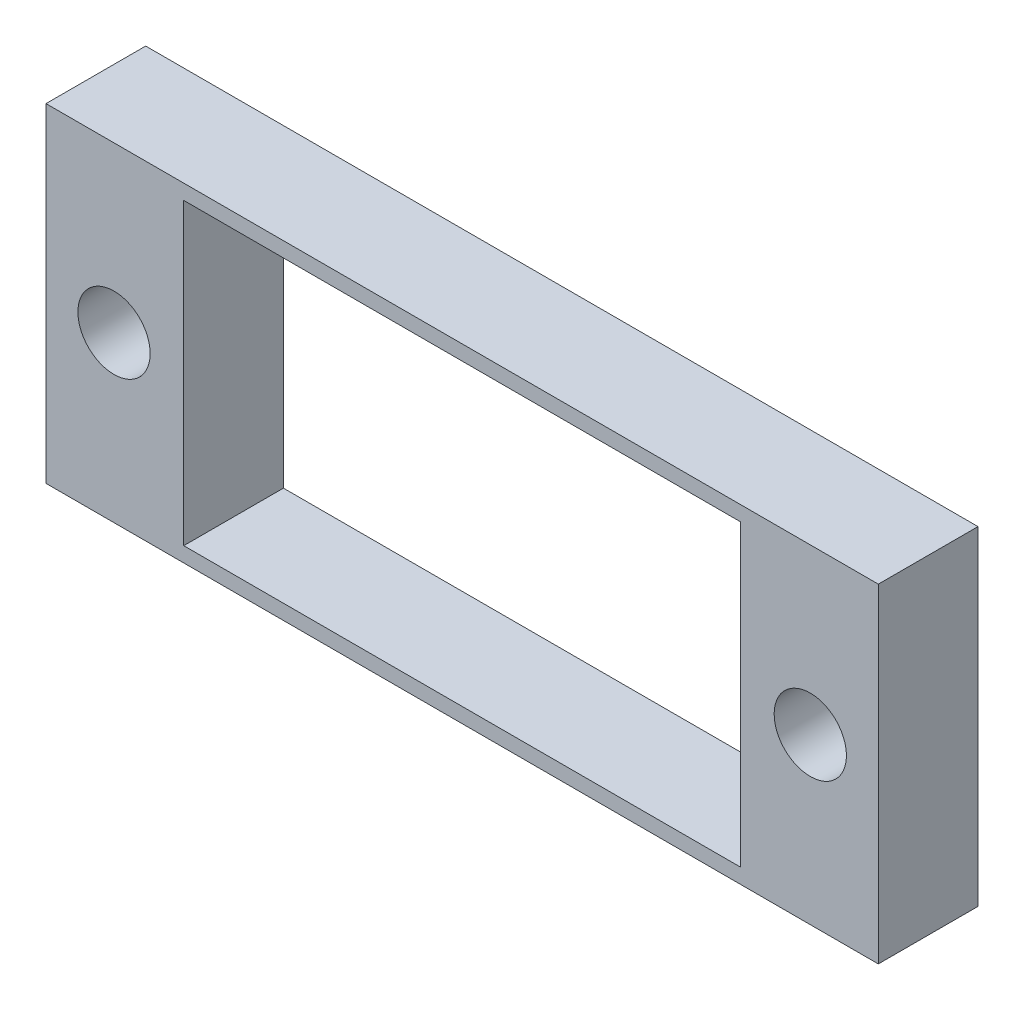
SolidWorks part; units mm, degrees
ref_plane "Front Plane" through (0, 0, 0) normal (0, 0, 1) x (1, 0, 0)
ref_plane "Top Plane" through (0, 0, 0) normal (0, 1, 0) x (1, 0, 0)
ref_plane "Right Plane" through (0, 0, 0) normal (1, 0, 0) x (0, 0, -1)
sketch "Sketch1" plane through (0, 0, 0) normal (0, 0, 1) x (1, 0, 0)
  line L0 (-16.7, 6.6) -> (16.7, 6.6)
  line L1 (-16.1, -6) -> (16.1, -6)
  line L2 (-16.1, -6) -> (-16.1, 6)
  line L3 (-16.1, 6) -> (16.1, 6)
  line L4 (16.1, -6) -> (16.1, 6)
  line L5 (-16.1, -6) -> (16.1, 6) construction
  line L6 (-16.1, 6) -> (16.1, -6) construction
  line L7 (16.7, -6.6) -> (16.7, 6.6)
  line L8 (-16.7, -6.6) -> (16.7, -6.6)
  line L9 (-16.7, -6.6) -> (-16.7, 6.6)
  point P0 (0, 0)
  dimension "D1" = 32.2
  dimension "D2" = 12
  dimension "D3" = 0.6
extrude "Boss-Extrude3" add sketch "Sketch1" along normal blind 4
sketch "Sketch3" plane through (0, 0, 4) normal (0, 0, 1) x (1, 0, 0)
  line L0 (-16.1, -6) -> (16.1, -6) construction
  line L1 (-16.1, 6) -> (-11.1724, 6)
  line L2 (-16.1, 6) -> (-16.1, -6)
  line L3 (-16.1, -6) -> (-11.1724, -6)
  line L4 (-11.1724, 6) -> (-11.1724, -6)
  line L5 (0, 0) -> (0, 12.195) construction
  line L6 (16.1, -6) -> (11.1724, -6)
  line L7 (11.1724, 6) -> (11.1724, -6)
  line L8 (16.1, 6) -> (11.1724, 6)
  line L9 (16.1, 6) -> (16.1, -6)
  dimension "D1" = 4.9276
extrude "Boss-Extrude4" add sketch "Sketch3" against normal through all
sketch "Sketch4" plane through (0, 0, 4) normal (0, 0, 1) x (1, 0, 0)
  line L0 (-16.7, 0) -> (19.2765, 0) construction
  line L1 (-16.7, 6.6) -> (-16.7, -6.6) construction
  line L2 (0, 0) -> (0, 9.0277) construction
  circle A0 centre (-13.97, 0) radius 1.45
  circle A1 centre (13.97, 0) radius 1.45
  point P9 (12.52, 0)
  point P12 (-12.52, 0)
  point P13 (-15.42, 0)
  dimension "D2" = 2.9
  dimension "D1" = 12.52
extrude "mounting holes" cut sketch "Sketch4" against normal through all
